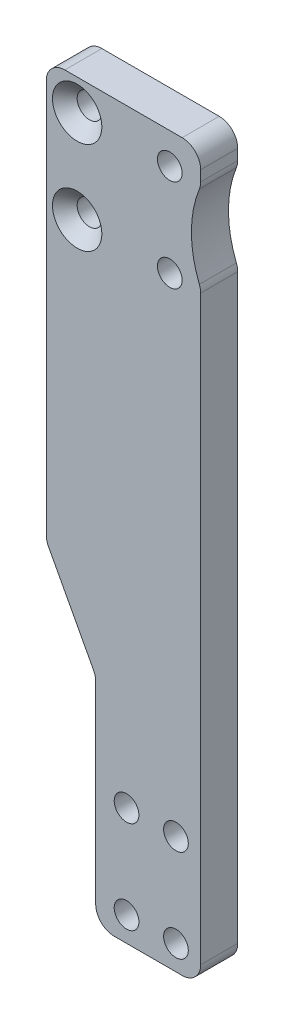
SolidWorks part; units mm, degrees
material "Thornel Mat VMA"
ref_plane "前视基准面" through (0, 0, 0) normal (0, 0, 1) x (1, 0, 0)
ref_plane "上视基准面" through (0, 0, 0) normal (0, 1, 0) x (1, 0, 0)
ref_plane "右视基准面" through (0, 0, 0) normal (1, 0, 0) x (0, 0, -1)
other "Configuration Table"
sketch "草图1" plane through (0, 0, 0) normal (0, 0, 1) x (1, 0, 0)
  line L0 (-10.5, 15) -> (-7, 87.5)
  line L1 (-12.5, -15) -> (12.5, -15)
  line L2 (-12.5, -15) -> (-12.5, 15)
  line L3 (-12.5, 15) -> (12.5, 15)
  line L4 (12.5, -15) -> (12.5, 15)
  line L5 (-12.5, -15) -> (12.5, 15)
  line L6 (-12.5, 15) -> (12.5, -15)
  line L7 (-7, 112.5) -> (18, 112.5)
  line L8 (-7, 112.5) -> (-7, 87.5)
  line L9 (-7, 87.5) -> (18, 87.5)
  line L10 (18, 112.5) -> (18, 87.5)
  line L11 (-7, 112.5) -> (18, 87.5)
  line L12 (-7, 87.5) -> (18, 112.5)
  line L17 (0, 0) -> (3.5, 0) construction
  line L19 (-2, 92.5) -> (13, 92.5) construction
  line L20 (-2, 92.5) -> (-2, 107.5) construction
  line L21 (-2, 107.5) -> (13, 107.5) construction
  line L22 (13, 92.5) -> (13, 107.5) construction
  line L23 (-2, 92.5) -> (13, 107.5) construction
  line L24 (-2, 107.5) -> (13, 92.5) construction
  line L25 (18, 87.5) -> (12.5, 15)
  line L27 (-0.5, -6) -> (7.5, -6) construction
  line L28 (-0.5, -6) -> (-0.5, 6) construction
  line L29 (-0.5, 6) -> (7.5, 6) construction
  line L30 (7.5, -6) -> (7.5, 6) construction
  line L31 (-0.5, -6) -> (7.5, 6) construction
  line L32 (-0.5, 6) -> (7.5, -6) construction
  circle A0 centre (13, 92.5) radius 2
  circle A1 centre (13, 107.5) radius 2
  circle A3 centre (-2, 107.5) radius 2
  circle A4 centre (-2, 92.5) radius 2
  circle A10 centre (7.5, 6) radius 2
  circle A11 centre (7.5, -6) radius 2
  circle A12 centre (-0.5, -6) radius 2
  circle A13 centre (-0.5, 6) radius 2
  point P6 (5.5, 100)
  point P16 (5.5, 100)
  dimension "D6" = 4
  dimension "D7" = 8
  dimension "D10" = 4
  dimension "D1" = 30
  dimension "D2" = 15
  dimension "D3" = 25
  dimension "D4" = 97.5
  dimension "D5" = 19.5
  dimension "D8" = 12
  dimension "D9" = 25
  dimension "D11" = 5
  dimension "D12" = 2
extrude "凸台-拉伸1" add sketch "草图1" along normal blind 6
sketch "草图2" plane through (0, 0, 6) normal (0, 0, 1) x (1, 0, 0)
  line L0 (5.5, 100) -> (34.5, 100) construction
  line L1 (13, 92.5) -> (-2, 107.5) construction
  circle A0 centre (34.5, 100) radius 18
  dimension "D2" = 36
  dimension "D1" = 29
extrude "切除-拉伸1" cut sketch "草图2" against normal blind 6
sketch "草图3" plane through (0, 0, 6) normal (0, 0, 1) x (1, 0, 0)
  line L0 (12.5, -15) -> (12.5, 15) construction
  line L1 (-10.5, 15) -> (-12.5, 15)
  line L2 (-10.5, 15) -> (-10.5, -15)
  line L3 (-10.5, -15) -> (-12.5, -15)
  line L4 (-12.5, 15) -> (-12.5, -15)
  line L5 (-12.5, -15) -> (12.5, -15)
  line L6 (-12.5, -15) -> (-12.5, -5)
  line L7 (-12.5, -5) -> (12.5, -5)
  line L8 (12.5, -15) -> (12.5, -5)
  line M9 (-12.5, -15) -> (12.5, -15)
  line M10 (12.5, -15) -> (12.5, 15)
  circle M13 centre (7.5, -6) radius 2
  circle M20 centre (-0.5, -6) radius 2
  dimension "D1" = 10
extrude "切除-拉伸2" cut sketch "草图3" against normal blind 10 contours L7 L2 M9 M10 M13 M20
sketch "草图4" plane through (0, 0, 6) normal (0, 0, 1) x (1, 0, 0)
  line L0 (-7, 103.074) -> (-7, -8.4388)
  line L1 (-7, 112.5) -> (-7, 87.5) construction
  line L13 (9.2321, -5) -> (12.5, -5)
  line L14 (12.5, -5) -> (12.5, 15)
  line L15 (12.5, 15) -> (18, 87.5)
  line L16 (18, 87.5) -> (18, 92.8063)
  line L17 (18, 107.1937) -> (18, 112.5)
  line L18 (18, 112.5) -> (-7, 112.5)
  line L19 (-7, 112.5) -> (-7, 87.5)
  line L20 (-7, 87.5) -> (-10.5, 15)
  line L21 (-10.5, 15) -> (-10.5, -5)
  line L22 (-10.5, -5) -> (-2.2321, -5)
  line L23 (1.2321, -5) -> (5.7679, -5)
  line L24 (9.2321, -5) -> (12.5, -5)
  line L25 (12.5, -5) -> (12.5, 15)
  line L26 (12.5, 15) -> (18, 87.5)
  line L27 (18, 87.5) -> (18, 92.8063)
  line L28 (18, 107.1937) -> (18, 112.5)
  line L29 (18, 112.5) -> (-7, 112.5)
  line L30 (-7, 112.5) -> (-7, 87.5)
  line L31 (-7, 87.5) -> (-10.5, 15)
  line L32 (-10.5, 15) -> (-10.5, -5)
  line L33 (-10.5, -5) -> (-2.2321, -5)
  line L34 (1.2321, -5) -> (5.7679, -5)
  arc A3 (9.2321, -5) -> (5.7679, -5) centre (7.5, -6) ccw
  arc A4 (18, 107.1937) -> (18, 92.8063) centre (34.5, 100) ccw
  arc A5 (1.2321, -5) -> (-2.2321, -5) centre (-0.5, -6) ccw
  arc A6 (9.2321, -5) -> (5.7679, -5) centre (7.5, -6) ccw
  arc A7 (18, 107.1937) -> (18, 92.8063) centre (34.5, 100) ccw
  arc A8 (1.2321, -5) -> (-2.2321, -5) centre (-0.5, -6) ccw
  line M31 (-7, 87.5) -> (-10.5, 15)
  line M32 (-10.5, 15) -> (-10.5, -5)
  line M33 (-10.5, -5) -> (-2.2321, -5)
  dimension "D1" = 0
extrude "切除-拉伸3" cut sketch "草图4" against normal blind 10 contours L0 M31 M32 M33
sketch "草图5" plane through (0, 0, 6) normal (0, 0, 1) x (1, 0, 0)
  line L0 (18, 87.5) -> (18, -5)
  line L1 (18, -5) -> (12.5, -5)
  line L2 (12.5, -5) -> (12.5, 15)
  line L3 (12.5, 15) -> (18, 87.5)
extrude "凸台-拉伸2" add sketch "草图5" against normal blind 6
sketch "草图6" plane through (0, 0, 6) normal (0, 0, 1) x (1, 0, 0)
  line L0 (9.2321, -5) -> (18, -5) construction
  line L1 (-4.0585, 9.4073) -> (11.7117, 9.4073)
  line L2 (-4.0585, 9.4073) -> (-4.0585, -5)
  line L3 (-4.0585, -5) -> (11.7117, -5)
  line L4 (11.7117, 9.4073) -> (11.7117, -5)
extrude "凸台-拉伸3" add sketch "草图6" against normal up to surface (6 mm away) up to face at (15, 107.5, 0)
sketch "草图7" plane through (0, 0, 6) normal (0, 0, 1) x (1, 0, 0)
  line L1 (-7, -5) -> (18, -5) construction
  line L2 (18, 92.8063) -> (18, -5) construction
  line L3 (-2, -1) -> (6, -1) construction
  line L4 (-2, -1) -> (-2, 14) construction
  line L5 (-2, 14) -> (6, 14) construction
  line L6 (6, -1) -> (6, 14) construction
  line L7 (-2, -1) -> (6, 14) construction
  line L8 (-2, 14) -> (6, -1) construction
  circle A0 centre (6, -1) radius 2
  circle A1 centre (6, 14) radius 2
  circle A2 centre (-2, 14) radius 2
  circle A3 centre (-2, -1) radius 2
  dimension "D4" = 4
  dimension "D1" = 8
  dimension "D2" = 15
  dimension "D3" = 4
  dimension "D5" = 12
extrude "切除-拉伸4" cut sketch "草图7" against normal blind 10
fillet "圆角1" radius 3 5 edges at (-7, 112.5, 3) (18, 107.1937, 3) (18, -5, 3) (-7, -5, 3) (18, 112.5, 3)
sketch "草图8" plane through (0, 0, 6) normal (0, 0, 1) x (1, 0, 0)
  line L0 (6, -1) -> (6, 14) construction
  line L1 (6, 14) -> (14, 14) construction
  line L2 (14, 14) -> (14, -1) construction
  line L3 (14, -1) -> (6, -1) construction
  circle A0 centre (14, 14) radius 2
  circle A1 centre (14, -1) radius 2
  circle A2 centre (6, 14) radius 2 construction
  dimension "D1" = 8
extrude "切除-拉伸5" cut sketch "草图8" against normal blind 10
sketch "草图9" plane through (0, 0, 6) normal (0, 0, 1) x (1, 0, 0)
  line L0 (-7, 109.5) -> (-7, -2) construction
  line L1 (-7, 30) -> (1, 30)
  line L2 (-7, 30) -> (-7, -5)
  line L3 (-7, -5) -> (1, -5)
  line L4 (1, 30) -> (1, -5)
  line L5 (-4, -5) -> (15, -5) construction
  circle A0 centre (6, 14) radius 2 construction
  dimension "D1" = 5
  dimension "D2" = 35
extrude "切除-拉伸6" cut sketch "草图9" against normal blind 10
sketch "草图10" plane through (0, 0, 6) normal (0, 0, 1) x (1, 0, 0)
  line L0 (1, 30) -> (-7, 30)
  line L1 (-7, 30) -> (-7, 45)
  line L2 (-7, 109.5) -> (-7, 30) construction
  line L3 (-7, 45) -> (1, 30)
  dimension "D1" = 15
extrude "切除-拉伸7" cut sketch "草图10" against normal blind 10
fillet "圆角2" radius 3 3 edges at (1, -5, 3) (1, 30, 3) (-7, 45, 3)
chamfer "倒角1" distance 2 angle 45 2 edges at (0, 107.5, 6) (0, 92.5, 6)
